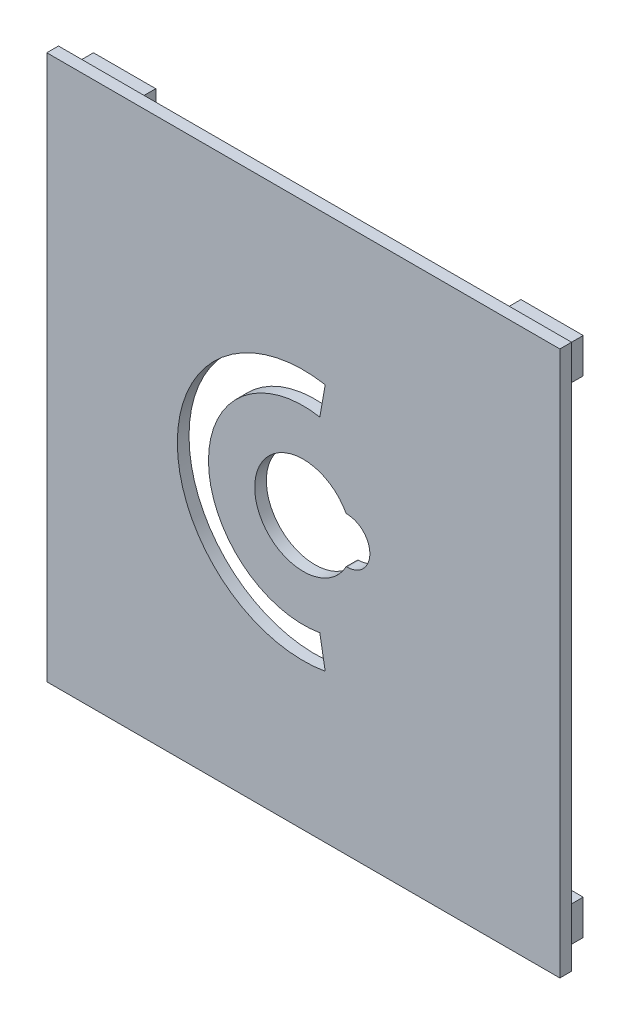
SolidWorks part; units mm, degrees
ref_plane "Front Plane" through (0, 0, 0) normal (0, 0, 1) x (1, 0, 0)
ref_plane "Top Plane" through (0, 0, 0) normal (0, 1, 0) x (1, 0, 0)
ref_plane "Right Plane" through (0, 0, 0) normal (1, 0, 0) x (0, 0, -1)
sketch "Sketch1" plane through (0, 0, 0) normal (0, 0, 1) x (1, 0, 0)
  line L0 (-10.75, -9.75) -> (121.1, -9.75) construction
  line L2 (121.1, -9.75) -> (55.175, -9.75)
  line L3 (121.1, -9.75) -> (121.1, 60.25)
  line L4 (121.1, 60.25) -> (55.175, 60.25)
  line L5 (55.175, -9.75) -> (55.175, 60.25)
  line L6 (-10.75, -9.75) -> (-10.75, 15.25) construction
  line L7 (-10.75, -9.75) -> (-10.75, 15.25) construction
  point P8 (55.175, -9.75)
extrude "Boss-Extrude1" add sketch "Sketch1" along normal blind 1.5 contours L5 L2 L3 L4
sketch "Sketch2" plane through (0, 0, 1.5) normal (0, 0, 1) x (1, 0, 0)
  line L4 (93.6475, 22.3) -> (93.7375, 22.3)
  line L5 (93.7375, 28.2) -> (93.6475, 28.2)
  line L6 (93.6475, 22.3) -> (93.7375, 22.3)
  line L7 (93.7375, 28.2) -> (93.6475, 28.2)
  arc A8 (93.7375, 22.3) -> (93.7375, 28.2) centre (93.7375, 25.25) ccw
  arc A9 (93.6475, 28.2) -> (93.6475, 22.3) centre (88.1375, 25.25) ccw
  arc A10 (93.7375, 22.3) -> (93.7375, 28.2) centre (93.7375, 25.25) ccw
  arc A11 (93.6475, 28.2) -> (93.6475, 22.3) centre (88.1375, 25.25) ccw
  dimension "D1" = 0.25
extrude "Cut-Extrude1" cut sketch "Sketch2" against normal up to next
ref_plane "Plane2" through (88.1375, 0, 0) normal (1, 0, 0) x (0, 0, -1)
ref_plane "Plane1" through (0, 25.25, 0) normal (0, 1, 0) x (1, 0, 0)
sketch "Sketch4" plane through (0, 0, 0) normal (0, 0, -1) x (-1, 0, 0)
  line L0 (-118.1, 57.25) -> (-118.1, 55.75)
  line L1 (-119.6, 58.75) -> (-111.6, 58.75)
  line L2 (-119.6, 58.75) -> (-119.6, 54.25)
  line L3 (-119.6, 54.25) -> (-111.6, 54.25)
  line L4 (-111.6, 58.75) -> (-111.6, 54.25)
  line L5 (-119.6, 58.75) -> (-119.6, 60.25) construction
  line L6 (-118.1, 55.75) -> (-113.1, 55.75)
  line L8 (-113.1, 57.25) -> (-113.1, 55.75)
  line L9 (-118.1, 57.25) -> (-113.1, 57.25)
  line L10 (-119.6, 58.75) -> (-121.1, 58.75) construction
  line L12 (-121.1, 60.25) -> (-55.175, 60.25) construction
  line L13 (-121.1, -9.75) -> (-121.1, 60.25) construction
  dimension "D1" = 1.5
  dimension "D2" = 5
  dimension "D3" = 1.5
extrude "Boss-Extrude2" add sketch "Sketch4" along normal blind 3
mirror "Mirror1" about plane through (88.1375, 0, 0) normal (1, 0, 0) of "Boss-Extrude2"
mirror "Mirror2" about plane through (0, 25.25, 0) normal (0, 1, 0) of "Mirror1", "Boss-Extrude2"
sketch "Sketch3" [suppressed] plane through (121.1, 0, 0) normal (1, 0, 0) x (0, 0, -1)
  line L0 (0, -9.75) -> (0, 60.25) construction
  line L1 (-1.5, 60.25) -> (6, 60.25)
  line L2 (-1.5, 60.25) -> (-1.5, 61.75)
  line L3 (-1.5, 61.75) -> (6, 61.75)
  line L4 (6, 60.25) -> (6, 61.75)
  line L5 (6, 60.25) -> (4.5, 58.75)
  line L7 (4.5, 58.75) -> (4.5, 60.25)
  dimension "D1" = 1.5
  dimension "D2" = 6
  dimension "D3" = 45
sketch "Sketch5" plane through (0, 0, 1.5) normal (0, 0, 1) x (1, 0, 0)
  line L0 (90.254, 37.2535) -> (90.9486, 41.1927)
  line L1 (90.254, 13.2465) -> (90.9486, 9.3073)
  line L6 (80.2871, 33.1004) -> (76.4143, 32.0995)
  line L7 (76.4143, 32.0995) -> (77.165, 29.1949)
  line L8 (77.165, 29.1949) -> (82.7493, 30.6382)
  line L9 (82.7493, 30.6382) -> (84.1926, 36.2225)
  line L10 (84.1926, 36.2225) -> (81.288, 36.9732)
  line L11 (81.288, 36.9732) -> (80.2871, 33.1004)
  line L12 (80.2871, 33.1004) -> (76.4143, 32.0995) construction
  line L13 (76.4143, 32.0995) -> (77.165, 29.1949) construction
  line L14 (77.165, 29.1949) -> (82.7493, 30.6382) construction
  line L15 (82.7493, 30.6382) -> (84.1926, 36.2225) construction
  line L16 (84.1926, 36.2225) -> (81.288, 36.9732) construction
  line L17 (81.288, 36.9732) -> (80.2871, 33.1004) construction
  line L21 (77.2375, 30.5) -> (77.2375, 25.8)
  line L22 (77.2375, 25.8) -> (78.4349, 25.8)
  line L23 (78.4349, 24.7) -> (77.2375, 24.7)
  line L24 (77.2375, 24.7) -> (77.2375, 20)
  line L25 (78.0875, 19.15) -> (82.8875, 19.15)
  line L26 (82.0375, 20) -> (82.0375, 30.5)
  line L27 (82.8875, 31.35) -> (78.0875, 31.35)
  line L28 (77.2375, 30.5) -> (77.2375, 25.8) construction
  line L29 (77.2375, 25.8) -> (78.4349, 25.8) construction
  line L30 (78.4349, 24.7) -> (77.2375, 24.7) construction
  line L31 (77.2375, 24.7) -> (77.2375, 20) construction
  line L32 (78.0875, 19.15) -> (82.8875, 19.15) construction
  line L33 (82.0375, 20) -> (82.0375, 30.5) construction
  line L34 (82.8875, 31.35) -> (78.0875, 31.35) construction
  arc A0 (90.9486, 41.1927) -> (90.9486, 9.3073) centre (88.1375, 25.25) ccw
  circle A2 centre (88.1375, 25.25) radius 0.8 construction
  circle A3 centre (88.1375, 25.25) radius 0.8 construction
  arc A4 (90.254, 37.2535) -> (90.254, 13.2465) centre (88.1375, 25.25) ccw
  arc A10 (78.4349, 24.7) -> (78.4349, 25.8) centre (79.3875, 25.25) ccw
  arc A11 (77.2375, 20) -> (78.0875, 19.15) centre (78.0875, 20) ccw
  arc A12 (82.0375, 20) -> (82.8875, 19.15) centre (82.8875, 20) ccw
  arc A13 (82.8875, 31.35) -> (82.0375, 30.5) centre (82.8875, 30.5) ccw
  arc A14 (78.0875, 31.35) -> (77.2375, 30.5) centre (78.0875, 30.5) ccw
  arc A15 (78.4349, 24.7) -> (78.4349, 25.8) centre (79.3875, 25.25) ccw construction
  arc A16 (77.2375, 20) -> (78.0875, 19.15) centre (78.0875, 20) ccw construction
  arc A17 (82.0375, 20) -> (82.8875, 19.15) centre (82.8875, 20) ccw construction
  arc A18 (82.8875, 31.35) -> (82.0375, 30.5) centre (82.8875, 30.5) ccw construction
  arc A19 (78.0875, 31.35) -> (77.2375, 30.5) centre (78.0875, 30.5) ccw construction
  dimension "D2" = 4
  dimension "D4" = 200
  dimension "D1" = 0
  dimension "D3" = 0
extrude "Cut-Extrude2" cut sketch "Sketch5" against normal through all
equation "\"D1@Boss-Extrude2\"=1.50mm+.25"
